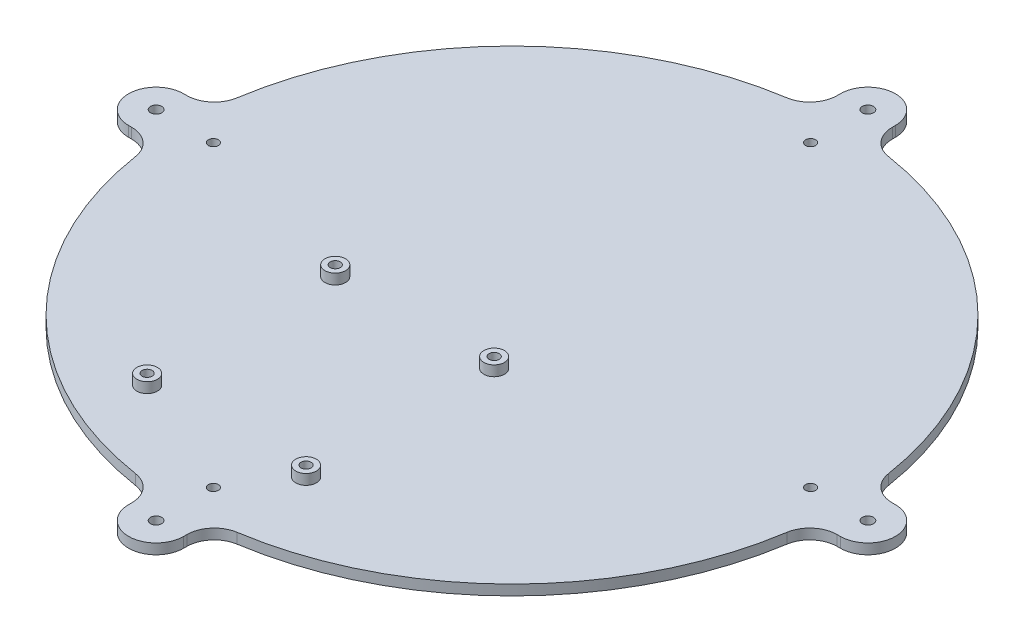
SolidWorks part; units mm, degrees
material "ABS"
ref_plane "Front Plane" through (0, 0, 0) normal (0, 0, 1) x (1, 0, 0)
ref_plane "Top Plane" through (0, 0, 0) normal (0, 1, 0) x (1, 0, 0)
ref_plane "Right Plane" through (0, 0, 0) normal (1, 0, 0) x (0, 0, -1)
sketch "Sketch1" plane through (0, 0, 0) normal (0, 1, 0) x (1, 0, 0)
  line L0 (-8.4836, 101.2452) -> (-8.4836, 109.7288)
  line L9 (8.4836, 109.7288) -> (8.4836, 101.2452)
  line L10 (109.7288, -8.4836) -> (101.2452, -8.4836)
  line L11 (101.2452, 8.4836) -> (109.7288, 8.4836)
  line L12 (-8.4836, -109.7288) -> (-8.4836, -101.2452)
  line L13 (8.4836, -101.2452) -> (8.4836, -109.7288)
  line L14 (-109.7288, 8.4836) -> (-101.2452, 8.4836)
  line L15 (-101.2452, -8.4836) -> (-109.7288, -8.4836)
  line L16 (0, 0) -> (0, 146.6167) construction
  circle A1 centre (0, 109.7288) radius 1.7272
  circle A2 centre (109.7288, 0) radius 1.7272
  circle A3 centre (0, -109.7288) radius 1.7272
  circle A4 centre (-109.7288, 0) radius 1.7272
  arc A6 (-8.4836, 101.2452) -> (-101.2452, 8.4836) centre (0, 0) ccw
  arc A10 (101.2452, 8.4836) -> (8.4836, 101.2452) centre (0, 0) ccw
  arc A11 (8.4836, -101.2452) -> (101.2452, -8.4836) centre (0, 0) ccw
  arc A12 (-101.2452, -8.4836) -> (-8.4836, -101.2452) centre (0, 0) ccw
  arc A13 (8.4836, 109.7288) -> (-8.4836, 109.7288) centre (0, 109.7288) ccw
  arc A14 (109.7288, -8.4836) -> (109.7288, 8.4836) centre (109.7288, 0) ccw
  arc A15 (-8.4836, -109.7288) -> (8.4836, -109.7288) centre (0, -109.7288) ccw
  arc A16 (-109.7288, 8.4836) -> (-109.7288, -8.4836) centre (-109.7288, 0) ccw
  point P17 (0, 0)
  point P36 (0, 0)
  point P44 (0, 0)
  dimension "D1" = 4
  dimension "D2" = 3.4544
  dimension "D4" = 4
  dimension "D5" = 8.4836
  dimension "D6" = 0
  dimension "D9" = 203.2
  dimension "D3" = 16.9672
extrude "Boss-Extrude1" add sketch "Sketch1" along normal blind 3.175
fillet "Fillet2" radius 8.4836 8 edges at (-8.4836, 1.5875, -101.2452) (8.4836, 1.5875, -101.2452) (101.2452, 1.5875, -8.4836) (101.2452, 1.5875, 8.4836) (8.4836, 1.5875, 101.2452) (-8.4836, 1.5875, 101.2452) (-101.2452, 1.5875, -8.4836) (-101.2452, 1.5875, 8.4836)
sketch "Sketch2" plane through (0, 3.175, 0) normal (0, 1, 0) x (1, 0, 0)
  line L1 (-15.6596, -100.3859) -> (15.6596, -100.3859) construction
  line L2 (11.4859, -74.9859) -> (-37.5141, -74.9859) construction
  line L3 (-37.5141, -74.9859) -> (-37.5141, -16.9859) construction
  line L4 (-37.5141, -16.9859) -> (11.4859, -16.9859) construction
  line L5 (11.4859, -16.9859) -> (11.4859, -74.9859) construction
  circle A1 centre (-37.5141, -74.9859) radius 3.175
  circle A2 centre (-37.5141, -16.9859) radius 3.175
  circle A4 centre (11.4859, -74.9859) radius 3.175
  circle A5 centre (11.4859, -16.9859) radius 3.175
  dimension "D1" = 6.35
  dimension "D2" = 49
  dimension "D4" = 6.35
  dimension "D5" = 58
  dimension "D6" = 6.35
  dimension "D7" = 6.35
  dimension "D8" = 88.9
  dimension "D3" = 50.8
extrude "Boss-Extrude2" add sketch "Sketch2" along normal blind 3.175
hole_wizard "CSK for M2.5 Cross Countersunk Head Screw4" positions "Sketch6" profile "Sketch7" countersink size "M2.5" standard "AS" end condition through all
sketch "Sketch6" plane through (0, 0, 0) normal (0, -1, 0) x (-1, 0, 0)
  point P0 (-11.4859, -16.9859)
  point P3 (37.5141, -16.9859)
  point P6 (37.5141, -74.9859)
  point P9 (-11.4859, -74.9859)
sketch "Sketch7" plane through (11.4859, 0, 16.9859) normal (1, 0, 0) x (0, 0, -1)
  line L0 (0, 0) -> (0, 6.35)
  line L1 (0, 6.35) -> (1.55, 6.35)
  line L2 (1.55, 6.35) -> (1.55, 0.9174)
  line L3 (1.55, 0.9174) -> (2.5, 0)
  line L5 (2.5, 0) -> (0, 0)
  line L6 (-1.55, 0.9174) -> (-2.5, 0) construction
  line L11 (0, -6.35) -> (0, 107.95) construction
  dimension "Thru Hole Dia." = 3.1
  dimension "Thru Hole Depth" = 6.35
  dimension "Near C'Sink Dia." = 5
  dimension "Near C'Sink Angle" = 92
sketch "Sketch8" plane through (0, 3.175, 0) normal (0, 1, 0) x (1, 0, 0)
  line L0 (0, -109.7288) -> (0, 109.7288) construction
  line L1 (0, 0) -> (109.7288, 0) construction
  circle A0 centre (0, 92.075) radius 2.7341
  arc A3 (100.3859, 15.6596) -> (15.6596, 100.3859) centre (0, 0) ccw construction
  circle A5 centre (0, 109.7288) radius 1.7272 construction
  circle A6 centre (0, -92.075) radius 2.7341
  circle A7 centre (0, -109.7288) radius 1.7272 construction
  circle A8 centre (-92.075, 0) radius 2.7341
  circle A9 centre (-109.7288, 0) radius 1.7272 construction
  circle A10 centre (92.075, 0) radius 2.7341
  point P24 (0, 0)
  dimension "D1" = 5.4683
  dimension "D2" = 92.075
  dimension "D3" = 17.6538
  dimension "D4" = 17.6538
  dimension "D5" = 92.075
  dimension "D7" = 92.075
  dimension "D8" = 17.6538
  dimension "D6" = 2
hole_wizard "CSK for M2.5 Cross Countersunk Head Screw7" positions "Sketch11" profile "Sketch12" countersink size "M2.5" standard "AS" end condition through all
sketch "Sketch11" plane through (0, 0, 0) normal (0, -1, 0) x (-1, 0, 0)
  point P0 (0, 92.075)
  point P5 (0, -92.075)
  point P9 (92.075, 0)
  point P12 (-92.075, 0)
sketch "Sketch12" plane through (0, 0, -92.075) normal (1, 0, 0) x (0, 0, -1)
  line L0 (0, 0) -> (0, 6.35)
  line L1 (0, 6.35) -> (1.55, 6.35)
  line L2 (1.55, 6.35) -> (1.55, 0.9174)
  line L3 (1.55, 0.9174) -> (2.5, 0)
  line L5 (2.5, 0) -> (0, 0)
  line L6 (-1.55, 0.9174) -> (-2.5, 0) construction
  line L11 (0, -6.35) -> (0, 107.95) construction
  dimension "Thru Hole Dia." = 3.1
  dimension "Thru Hole Depth" = 6.35
  dimension "Near C'Sink Dia." = 5
  dimension "Near C'Sink Angle" = 92
